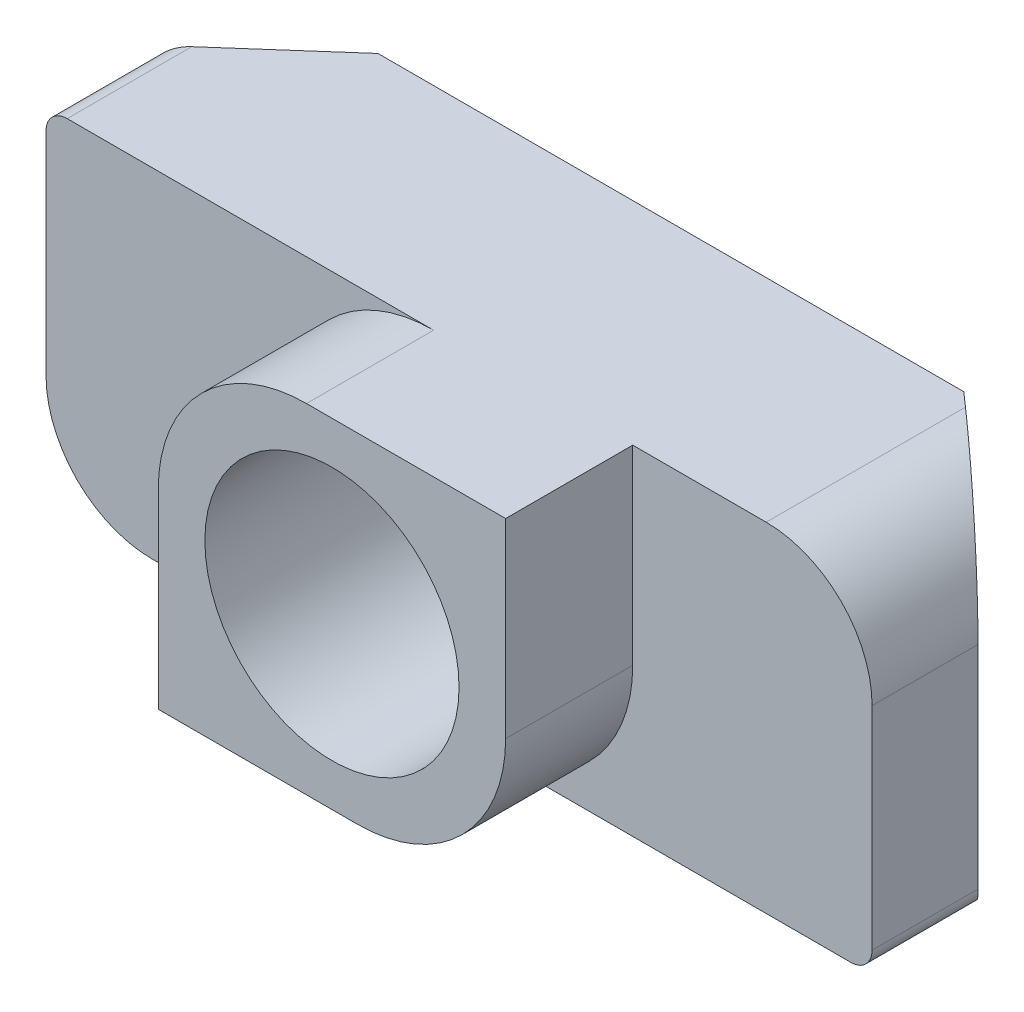
SolidWorks part; units mm, degrees
ref_plane "前视基准面" through (0, 0, 0) normal (0, 0, 1) x (1, 0, 0)
ref_plane "上视基准面" through (0, 0, 0) normal (0, 1, 0) x (1, 0, 0)
ref_plane "右视基准面" through (0, 0, 0) normal (1, 0, 0) x (0, 0, -1)
sketch "草图1" plane through (0, 0, 0) normal (0, 0, 1) x (1, 0, 0)
  line L1 (-9.75, -4) -> (9.75, -4)
  line L2 (-9.75, -4) -> (-9.75, 4)
  line L3 (-9.75, 4) -> (9.75, 4)
  line L4 (9.75, -4) -> (9.75, 4)
  line L5 (-9.75, -4) -> (9.75, 4) construction
  line L6 (-9.75, 4) -> (9.75, -4) construction
  point P0 (0, 0)
  dimension "D1" = 19.5
  dimension "D2" = 8
extrude "凸台-拉伸1" add sketch "草图1" along normal blind 5
fillet "圆角1" radius 2.5 2 edges at (9.75, 4, 2.5) (-9.75, -4, 2.5)
fillet "圆角2" radius 0.5 2 edges at (9.75, -4, 2.5) (-9.75, 4, 2.5)
sketch "草图2" plane through (0, -4, 0) normal (0, -1, 0) x (1, 0, 0)
  line L0 (-9.75, 2.5) -> (-6.9141, 0)
  line L1 (-9.75, 0) -> (-9.75, 5) construction
  line L2 (-7.25, 0) -> (9.25, 0) construction
  line L3 (-9.75, 2.5) -> (-9.75, 0)
  line L4 (-9.75, 0) -> (-6.9141, 0)
extrude "切除-拉伸2" cut sketch "草图2" against normal through all
mirror "镜向1" about plane through (0, 0, 0) normal (1, 0, 0) of "切除-拉伸2"
sketch "草图3" plane through (0, 0, 5) normal (0, 0, 1) x (1, 0, 0)
  line L0 (7.25, 4) -> (-9.25, 4) construction
  line L1 (-4.1, -4) -> (4.1, -4)
  line L2 (-4.1, -4) -> (-4.1, 4)
  line L3 (-4.1, 4) -> (4.1, 4)
  line L4 (4.1, -4) -> (4.1, 4)
  line L5 (-4.1, -4) -> (4.1, 4) construction
  line L6 (-4.1, 4) -> (4.1, -4) construction
  point P0 (0, 0)
  dimension "D1" = 8.2
extrude "凸台-拉伸2" add sketch "草图3" along normal blind 3
fillet "圆角3" radius 3.5 2 edges
sketch "草图4" plane through (0, 0, 8) normal (0, 0, 1) x (1, 0, 0)
  circle A0 centre (0, 0) radius 3
  dimension "D1" = 6
extrude "切除-拉伸3" cut sketch "草图4" against normal through all
